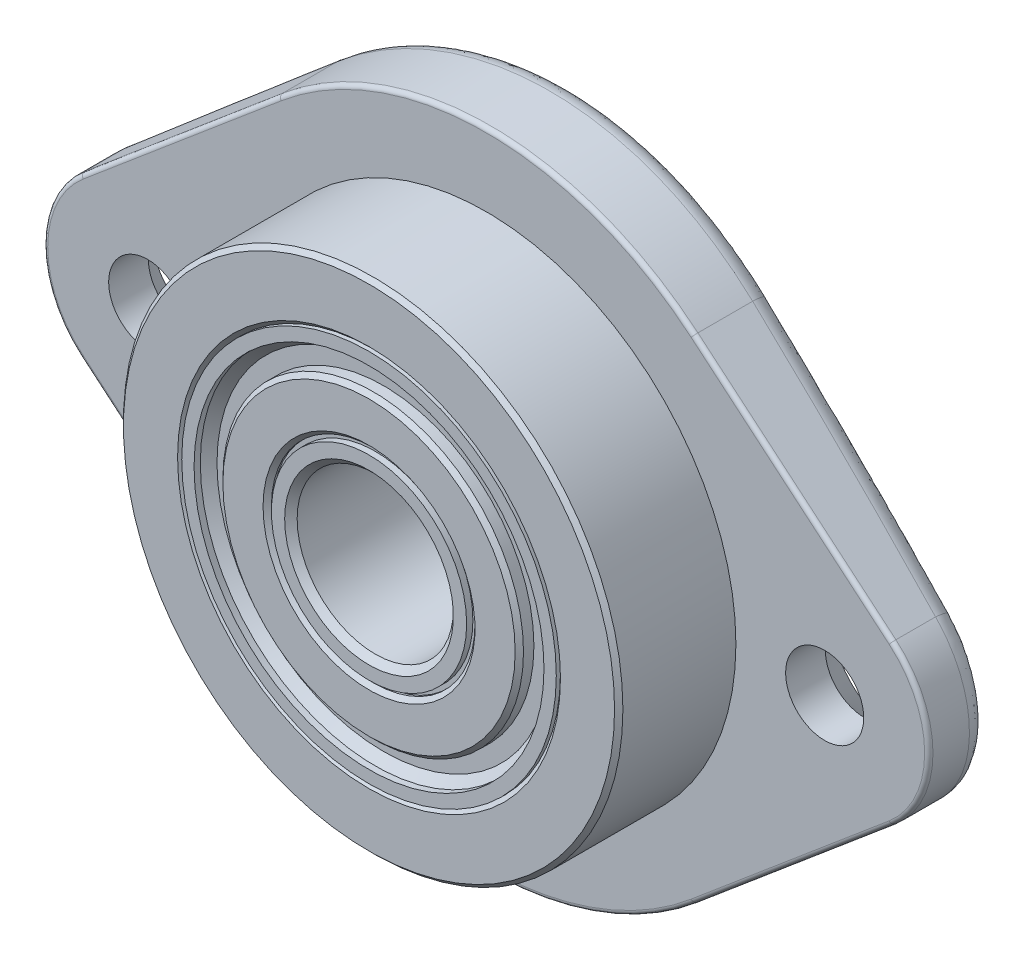
SolidWorks part; units mm, degrees
ref_plane "Front Plane" through (0, 0, 0) normal (0, 0, 1) x (1, 0, 0)
ref_plane "Top Plane" through (0, 0, 0) normal (0, 1, 0) x (1, 0, 0)
ref_plane "Right Plane" through (0, 0, 0) normal (1, 0, 0) x (0, 0, -1)
sketch "Sketch1" plane through (0, 0, 0) normal (0, 0, 1) x (1, 0, 0)
  line L0 (-26.9875, 0) -> (26.9875, 0) construction
  line L1 (0, 0) -> (0, 19.6453) construction
  line L2 (24.7284, 4.8567) -> (12.6561, 15.0253)
  line L3 (24.7284, -4.8567) -> (12.6561, -15.0253)
  line L4 (-20.6375, 0) -> (20.6375, 0) construction
  line L5 (-24.7284, 4.8567) -> (-12.6561, 15.0253)
  line L6 (-24.7284, -4.8567) -> (-12.6561, -15.0253)
  line L7 (-18.2562, 0) -> (-15.2251, 0) construction
  circle A0 centre (0, 0) radius 4.7625
  circle A1 centre (-20.6375, 0) radius 2.3813
  circle A2 centre (20.6375, 0) radius 2.3813
  arc A3 (-24.7284, 4.8567) -> (-24.7284, -4.8567) centre (-20.6375, 0) ccw
  arc A4 (24.7284, 4.8567) -> (24.7284, -4.8567) centre (20.6375, 0) cw
  circle A5 centre (0, 0) radius 19.6453
  circle A6 centre (0, 0) radius 15.2251
  circle A7 centre (0, 0) radius 5.9531
  circle A8 centre (0, 0) radius 11.4188
  point P26 (0, 4.7625)
  point P27 (0, 11.4188)
  point P28 (0, 5.9531)
  dimension "D2" = 30.4502
  dimension "D" = 39.2906
  dimension "F" = 4.7625
  dimension "shaft dia" = 9.525
  dimension "D8" = 11.9063
  dimension "D10" = 22.8377
  dimension "E" = 41.275
  dimension "B" = 53.975
sketch "Sketch3" plane through (0, 0, 0) normal (1, 0, 0) x (0, 0, -1)
  line L0 (-6.1516, 5.9531) -> (-5.7706, 5.9531)
  line L1 (-6.1516, 11.4188) -> (0.9922, 11.4188)
  line L2 (-6.1516, 11.4188) -> (-6.1516, 10.6677)
  line L3 (-6.1516, 4.7625) -> (0.9922, 4.7625)
  line L5 (-5.7706, 5.9531) -> (-5.7706, 6.2071)
  line L6 (-5.7706, 6.2071) -> (-6.1516, 6.2071)
  line L7 (-6.1516, 9.1655) -> (-5.2626, 9.1655)
  line L8 (-5.2626, 9.1655) -> (-5.2626, 10.6677)
  line L9 (-5.2626, 10.6677) -> (-6.1516, 10.6677)
  line L10 (-6.1516, 5.9531) -> (-6.1516, 4.7625)
  line L11 (-6.1516, 9.1655) -> (-6.1516, 6.2071)
  line L12 (0.9922, 11.4188) -> (0.9922, 4.7625)
  line L23 (-6.1516, 0) -> (6.1516, 0) construction
  point P14 (0.9922, 0)
  dimension "D1" = 0.254
  dimension "C" = 12.3031
  dimension "D2" = 0.381
  dimension "D3" = 6.6563
  dimension "D4" = 2.9584
  dimension "D5" = 0.889
  dimension "D6" = 2.2533
  dimension "D7" = 0.7511
  dimension "G" = 5.1594
revolve "Revolve1" add sketch "Sketch3" angle 360 about L23
chamfer "Chamfer2" distance 0.381 angle 45 1 edges at (4.7625, 0, 6.1516)
chamfer "Chamfer3" distance 0.254 angle 45 2 edges at (9.1655, 0, 6.1516) (6.2071, 0, 6.1516)
chamfer "Chamfer4" distance 0.508 angle 45 1 edges at (10.6677, 0, 5.2626)
sketch "Sketch2" plane through (0, 0, 0) normal (0, 0, 1) x (1, 0, 0)
  line L0 (24.7284, 4.8567) -> (12.6561, 15.0253) construction
  line L1 (24.7284, -4.8567) -> (12.6561, -15.0253) construction
  line L2 (-24.7284, -4.8567) -> (-12.6561, -15.0253) construction
  line L3 (-24.7284, 4.8567) -> (-12.6561, 15.0253) construction
  line L4 (24.7284, 4.8567) -> (12.6561, 15.0253)
  line L5 (24.7284, -4.8567) -> (12.6561, -15.0253)
  line L6 (-24.7284, -4.8567) -> (-12.6561, -15.0253)
  line L7 (-24.7284, 4.8567) -> (-12.6561, 15.0253)
  arc A0 (24.7284, -4.8567) -> (24.7284, 4.8567) centre (20.6375, 0) ccw construction
  arc A1 (-24.7284, 4.8567) -> (-24.7284, -4.8567) centre (-20.6375, 0) ccw construction
  circle A2 centre (0, 0) radius 19.6453 construction
  arc A3 (24.7284, -4.8567) -> (24.7284, 4.8567) centre (20.6375, 0) ccw
  arc A4 (-24.7284, 4.8567) -> (-24.7284, -4.8567) centre (-20.6375, 0) ccw
  arc A5 (12.6561, 15.0253) -> (-12.6561, 15.0253) centre (0, 0) ccw
  arc A6 (-12.6561, -15.0253) -> (12.6561, -15.0253) centre (0, 0) ccw
  circle A7 centre (20.6375, 0) radius 2.3813 construction
  circle A8 centre (-20.6375, 0) radius 2.3813 construction
  circle A9 centre (20.6375, 0) radius 2.3813
  circle A10 centre (-20.6375, 0) radius 2.3813
extrude "Extrude1" add sketch "Sketch2" along normal blind 5.1594 from vertex at -6.1516 separate body starting at point (0, 0, -6.1516)
sketch "Sketch9" plane through (0, 0, -0.9922) normal (0, 0, 1) x (1, 0, 0)
  circle A0 centre (0, 0) radius 15.2251 construction
  circle A1 centre (0, 0) radius 11.4188 construction
  circle A2 centre (0, 0) radius 15.2251
  circle A3 centre (0, 0) radius 11.4188
extrude "Boss-Extrude2" add sketch "Sketch9" along normal up to vertex (7.1437 mm away) up to point (0, 0, 6.1516)
chamfer "Chamfer5" distance 0.254 angle 45 2 edges at (15.2251, 0, 6.1516) (11.4188, 0, 6.1516)
sketch "Sketch10" plane through (0, 0, -6.1516) normal (0, 0, -1) x (-1, 0, 0)
  circle A0 centre (-20.6375, 0) radius 4.7625
  circle A1 centre (20.6375, 0) radius 4.7625
  dimension "D1" = 9.525
extrude "Cut-Extrude2" cut sketch "Sketch10" against normal through all draft 41
sketch "Sketch5" plane through (0, 0, 0) normal (0, 1, 0) x (1, 0, 0)
  line L0 (12.6561, 6.1516) -> (-12.6561, 6.1516) construction
  line L2 (-26.9875, 4.6037) -> (-26.9875, 6.6596)
  line L3 (-26.9875, 6.6596) -> (26.9875, 6.6596)
  line L4 (26.9875, 4.6037) -> (26.9875, 6.6596)
  line L7 (-12.6561, 6.1516) -> (-24.7284, 6.1516) construction
  line L8 (26.9875, 6.1516) -> (24.7284, 6.1516) construction
  arc A0 (-26.9875, 4.6037) -> (26.9875, 4.6037) centre (0, -229.898) cw
  dimension "D1" = 1.5478
  dimension "D2" = 0.508
extrude "Cut-Extrude1" cut sketch "Sketch5" against normal through all both and the other way through all
fillet "Fillet2" radius 1.27 8 edges at (-18.6984, 9.9358, -5.4098) (0.5063, 19.6388, -6.151) (18.6984, 9.9358, -5.4098) (26.9257, 0.8838, -4.6109) (18.6984, -9.9358, -5.4098) (-0.5063, -19.6388, -6.151) (-18.6984, -9.9358, -5.4098) (-26.9257, -0.8838, -4.6109)
fillet "Fillet3" radius 0.254 8 edges at (18.6922, 9.941, -0.9922) (26.9875, 0, -0.9922) (18.6922, -9.941, -0.9922) (0, -19.6453, -0.9922) (-18.6922, -9.941, -0.9922) (-26.9875, 0, -0.9922) (-18.6922, 9.941, -0.9922) (0, 19.6453, -0.9922)
equation "\"D8@Sketch1\"=\"shaft dia@Sketch1\"*1.25"
equation "\"D4@Sketch3\"=\"D3@Sketch3\"/2.25"
equation "\"D1@Sketch5\" = \"G@Extrude1\"*.3"
equation "\"D7@Sketch3\"= \"D6@Sketch3\" / 3"
equation "\"D1@Sketch10\"=\"F@Sketch1\"*2"
equation "\"D2@Sketch1\"=\"D@Sketch1\"*.775"
equation "\"D10@Sketch1\"=\"D2@Sketch1\"*.75"
